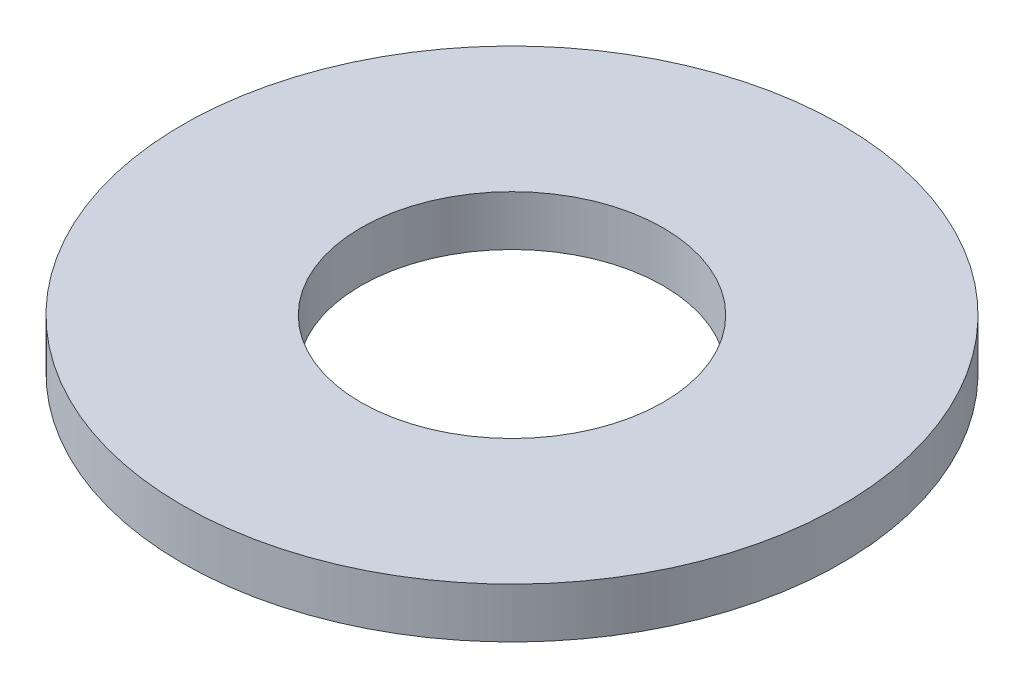
SolidWorks part; units mm, degrees
ref_plane "Front Plane" through (0, 0, 0) normal (0, 0, 1) x (1, 0, 0)
ref_plane "Top Plane" through (0, 0, 0) normal (0, 1, 0) x (1, 0, 0)
ref_plane "Right Plane" through (0, 0, 0) normal (1, 0, 0) x (0, 0, -1)
sketch "Sketch1" plane through (0, 0, 0) normal (0, 1, 0) x (1, 0, 0)
  circle A0 centre (0, 0) radius 9.525
  dimension "OD" = 19.05
extrude "Boss-Extrude1" add sketch "Sketch1" along normal blind 1.4478
sketch "Sketch5" plane through (0, 1.4478, 0) normal (0, 1, 0) x (-1, 0, 0)
  circle A0 centre (0, 0) radius 4.3688
  dimension "ID" = 8.7376
extrude "Cut-Extrude1" cut sketch "Sketch5" against normal through all
